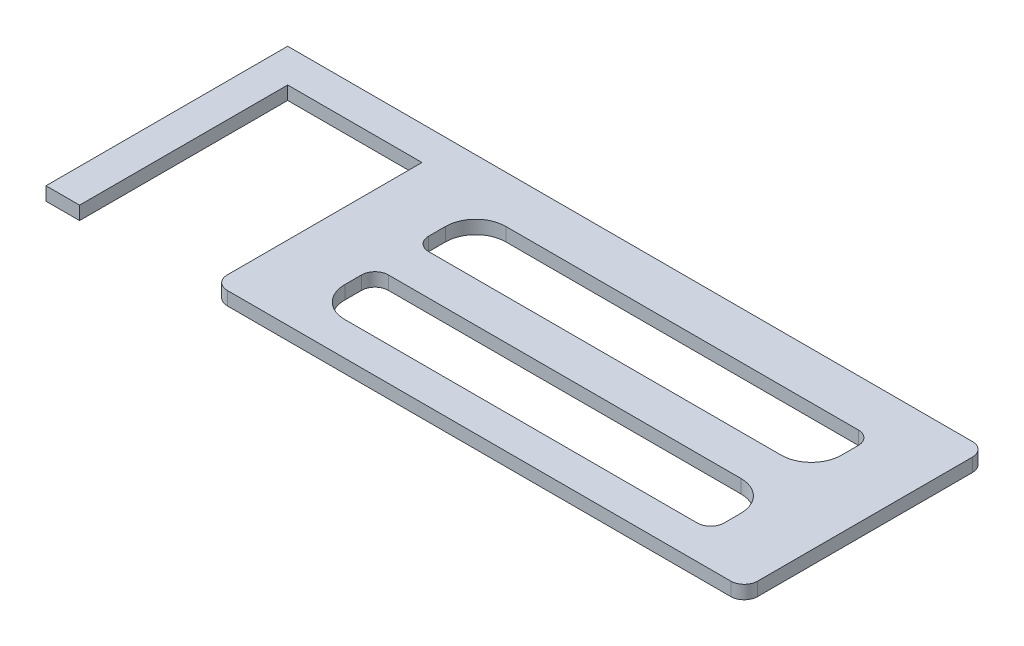
SolidWorks part; units mm, degrees
material "Hexcel AS4C (3000 Filaments)"
ref_plane "Front Plane" through (0, 0, 0) normal (0, 0, 1) x (1, 0, 0)
ref_plane "Top Plane" through (0, 0, 0) normal (0, 1, 0) x (1, 0, 0)
ref_plane "Right Plane" through (0, 0, 0) normal (1, 0, 0) x (0, 0, -1)
sketch "Sketch1" plane through (0, 0, 0) normal (0, 1, 0) x (1, 0, 0)
  line L0 (-39.5, -16) -> (-39.5, 13)
  line L1 (-37.5, -18) -> (37.5, -18)
  line L3 (-39.5, 18) -> (37.5, 18)
  line L4 (39.5, -16) -> (39.5, 16)
  line L5 (-39.5, -18) -> (39.5, 18) construction
  line L6 (-39.5, 18) -> (39.5, -18) construction
  line L7 (-39.5, 13) -> (-59.5, 13)
  line L8 (-39.5, 18) -> (-64.5, 18)
  line L9 (-64.5, 18) -> (-64.5, -18)
  line L10 (-64.5, -18) -> (-59.5, -18)
  line L11 (-59.5, -18) -> (-59.5, 13)
  line L12 (-25, 11) -> (27.5, 11)
  line L16 (-29.5, 6.5) -> (-29.5, 4)
  line L18 (29.5, 9) -> (29.5, 6.5)
  line L19 (-27.5, 2) -> (25, 2)
  line L20 (-27.5, -4) -> (25, -4)
  line L21 (-29.5, -6) -> (-29.5, -8.5)
  line L22 (29.5, -8.5) -> (29.5, -11)
  line L23 (-25, -13) -> (27.5, -13)
  arc A0 (-25, -13) -> (-29.5, -8.5) centre (-25, -8.5) cw
  arc A1 (25, -4) -> (29.5, -8.5) centre (25, -8.5) cw
  arc A2 (29.5, 6.5) -> (25, 2) centre (25, 6.5) cw
  arc A3 (-29.5, 6.5) -> (-25, 11) centre (-25, 6.5) cw
  arc A4 (37.5, 18) -> (39.5, 16) centre (37.5, 16) cw
  arc A5 (27.5, -13) -> (29.5, -11) centre (27.5, -11) ccw
  arc A6 (27.5, 11) -> (29.5, 9) centre (27.5, 9) cw
  arc A7 (-29.5, -6) -> (-27.5, -4) centre (-27.5, -6) cw
  arc A8 (-27.5, 2) -> (-29.5, 4) centre (-27.5, 4) cw
  arc A9 (37.5, -18) -> (39.5, -16) centre (37.5, -16) ccw
  arc A10 (-37.5, -18) -> (-39.5, -16) centre (-37.5, -16) cw
  point P0 (0, 0)
  dimension "D1" = 4.5
  dimension "D2" = 2
extrude "Boss-Extrude1" add sketch "Sketch1" along normal blind 2
